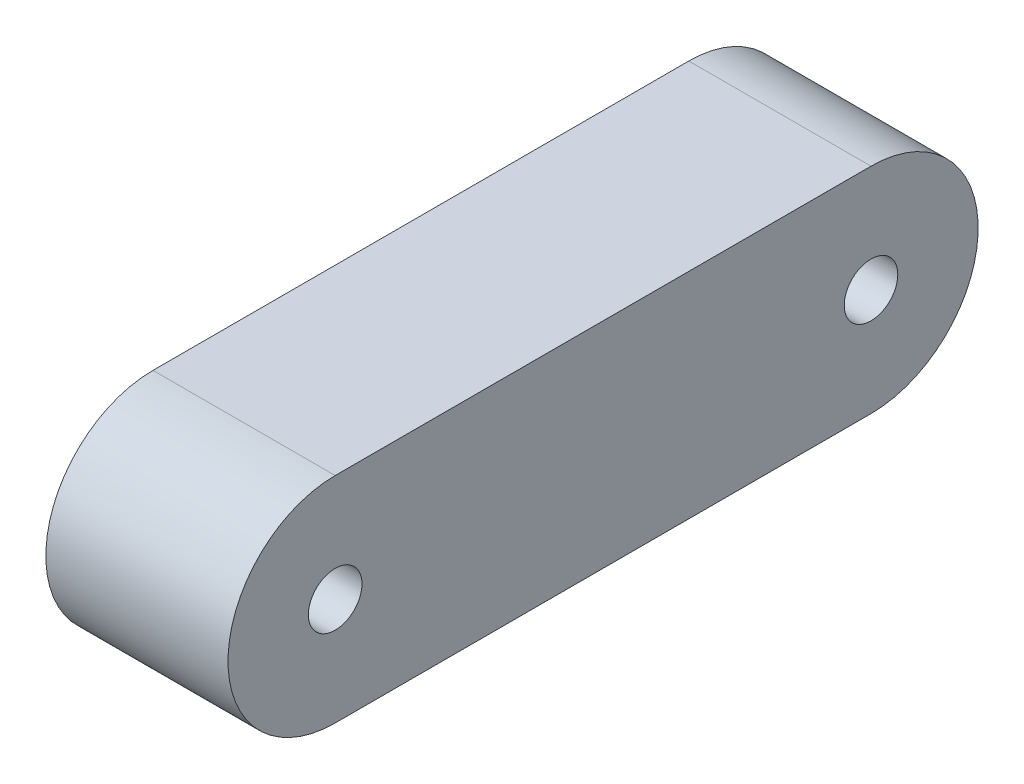
SolidWorks part; units mm, degrees
ref_plane "Alzado" through (0, 0, 0) normal (0, 0, 1) x (1, 0, 0)
ref_plane "Planta" through (0, 0, 0) normal (0, 1, 0) x (1, 0, 0)
ref_plane "Vista lateral" through (0, 0, 0) normal (1, 0, 0) x (0, 0, -1)
sketch "Croquis1" plane through (0, 0, 0) normal (1, 0, 0) x (0, 0, -1)
  line L0 (-25, 0) -> (25, 0) construction
  line L1 (-25, 10) -> (25, 10)
  line L2 (-25, -10) -> (25, -10)
  arc A0 (-25, 10) -> (-25, -10) centre (-25, 0) ccw
  arc A1 (25, -10) -> (25, 10) centre (25, 0) ccw
  circle A2 centre (-25, 0) radius 2.5
  circle A3 centre (25, 0) radius 2.5
  point P4 (0, 0)
  dimension "D1" = 20
  dimension "D3" = 5
  dimension "D2" = 50
extrude "Saliente-Extruir1" add sketch "Croquis1" along normal mid plane 17
